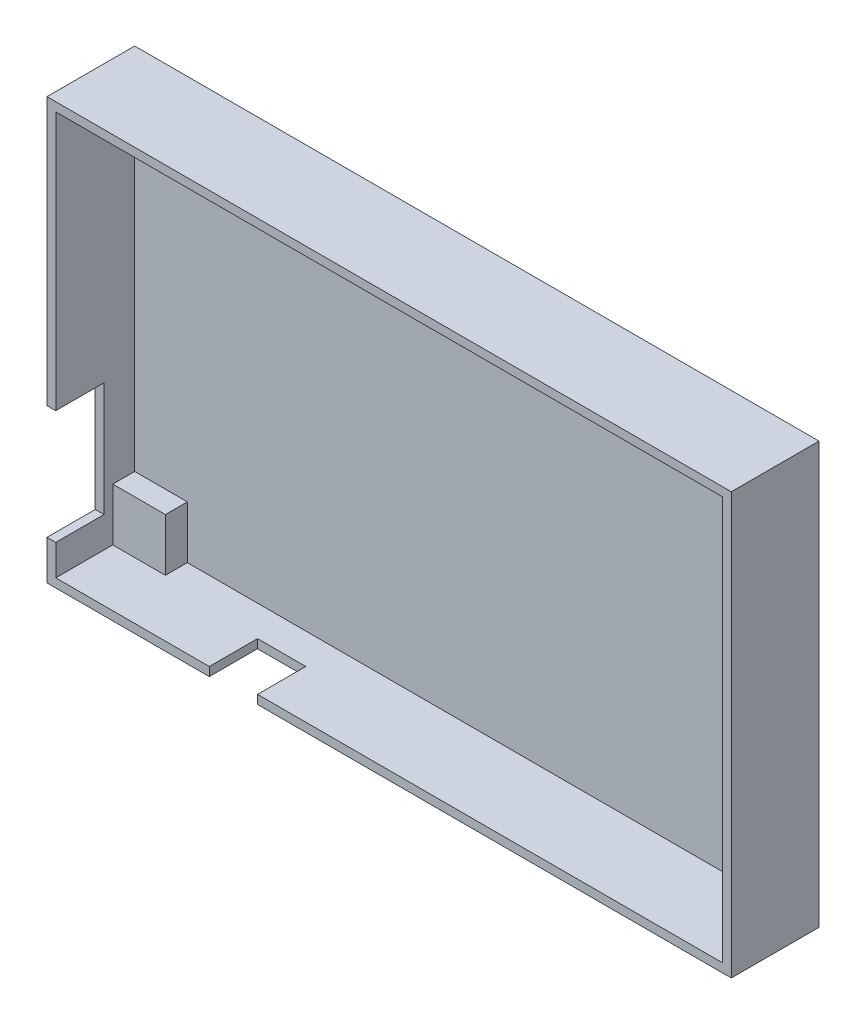
SolidWorks part; units mm, degrees
ref_plane "Plan de face" through (0, 0, 0) normal (0, 0, 1) x (1, 0, 0)
ref_plane "Plan de dessus" through (0, 0, 0) normal (0, 1, 0) x (1, 0, 0)
ref_plane "Plan de droite" through (0, 0, 0) normal (1, 0, 0) x (0, 0, -1)
sketch "Esquisse1" plane through (0, 0, 0) normal (0, 0, 1) x (1, 0, 0)
  line L1 (-70.1386, 46.5558) -> (85.8614, 46.5558)
  line L2 (-70.1386, 46.5558) -> (-70.1386, -49.4442)
  line L3 (-70.1386, -49.4442) -> (85.8614, -49.4442)
  line L4 (85.8614, 46.5558) -> (85.8614, -49.4442)
  dimension "D1" = 96
  dimension "D2" = 156
extrude "Boss.-Extru.1" add sketch "Esquisse1" along normal blind 2
sketch "Esquisse2" plane through (0, 0, 2) normal (0, 0, 1) x (1, 0, 0)
  line L1 (-70.1386, 46.5558) -> (85.8614, 46.5558)
  line L2 (-70.1386, 46.5558) -> (-70.1386, -49.4442)
  line L3 (-70.1386, -49.4442) -> (85.8614, -49.4442)
  line L4 (85.8614, 46.5558) -> (85.8614, -49.4442)
  line L5 (-68.1386, 44.5558) -> (83.8614, 44.5558)
  line L6 (-68.1386, 44.5558) -> (-68.1386, -47.4442)
  line L7 (-68.1386, -47.4442) -> (83.8614, -47.4442)
  line L8 (83.8614, 44.5558) -> (83.8614, -47.4442)
  dimension "D1" = 2
  dimension "D2" = 2
  dimension "D3" = 2
  dimension "D4" = 2
extrude "Boss.-Extru.2" add sketch "Esquisse2" along normal blind 18
sketch "Esquisse3" plane through (0, 0, 2) normal (0, 0, 1) x (1, 0, 0)
  line L0 (-68.1386, 44.5558) -> (-68.1386, -47.4442) construction
  line L1 (-68.1386, 44.5558) -> (-56.1386, 44.5558)
  line L2 (-68.1386, 44.5558) -> (-68.1386, 32.5558)
  line L3 (-68.1386, 32.5558) -> (-56.1386, 32.5558)
  line L4 (-56.1386, 44.5558) -> (-56.1386, 32.5558)
  line L5 (83.8614, -47.4442) -> (71.8614, -47.4442)
  line L6 (83.8614, -47.4442) -> (83.8614, -35.4442)
  line L7 (83.8614, -35.4442) -> (71.8614, -35.4442)
  line L8 (71.8614, -47.4442) -> (71.8614, -35.4442)
  line L9 (83.8614, 44.5558) -> (71.8614, 44.5558)
  line L10 (83.8614, 44.5558) -> (83.8614, 32.5558)
  line L11 (83.8614, 32.5558) -> (71.8614, 32.5558)
  line L12 (71.8614, 44.5558) -> (71.8614, 32.5558)
  line L13 (-68.1386, -47.4442) -> (-56.1386, -47.4442)
  line L14 (-68.1386, -47.4442) -> (-68.1386, -35.4442)
  line L15 (-68.1386, -35.4442) -> (-56.1386, -35.4442)
  line L16 (-56.1386, -47.4442) -> (-56.1386, -35.4442)
  line L17 (-68.1386, -47.4442) -> (83.8614, -47.4442) construction
  dimension "D3" = 12
extrude "Boss.-Extru.3" add sketch "Esquisse3" along normal blind 5
sketch3d "Esquisse3D1" plane through (0, 0, 0) normal (0, 0, 1) x (1, 0, 0)
  dimension "D1" = 2
sketch "Esquisse4" plane through (0, 0, 9) normal (0, 0, 1) x (1, 0, 0)
  line L0 (-68.1386, -47.4442) -> (83.8614, -47.4442) construction
  line L1 (-74.9001, -40.4442) -> (-62.4118, -40.4442)
  line L2 (-74.9001, -40.4442) -> (-74.9001, -14.4442)
  line L3 (-74.9001, -14.4442) -> (-62.4118, -14.4442)
  line L4 (-62.4118, -40.4442) -> (-62.4118, -14.4442)
  line L5 (-68.1386, 32.5558) -> (-68.1386, -35.4442) construction
  line L6 (-33.1386, -43.6717) -> (-22.1386, -43.6717)
  line L7 (-33.1386, -43.6717) -> (-33.1386, -54.89)
  line L8 (-33.1386, -54.89) -> (-22.1386, -54.89)
  line L9 (-22.1386, -43.6717) -> (-22.1386, -54.89)
  dimension "D1" = 7
  dimension "D2" = 33
  dimension "D3" = 35
  dimension "D4" = 46
extrude "Enlèv. mat.-Extru.1" cut sketch "Esquisse4" along normal through all
